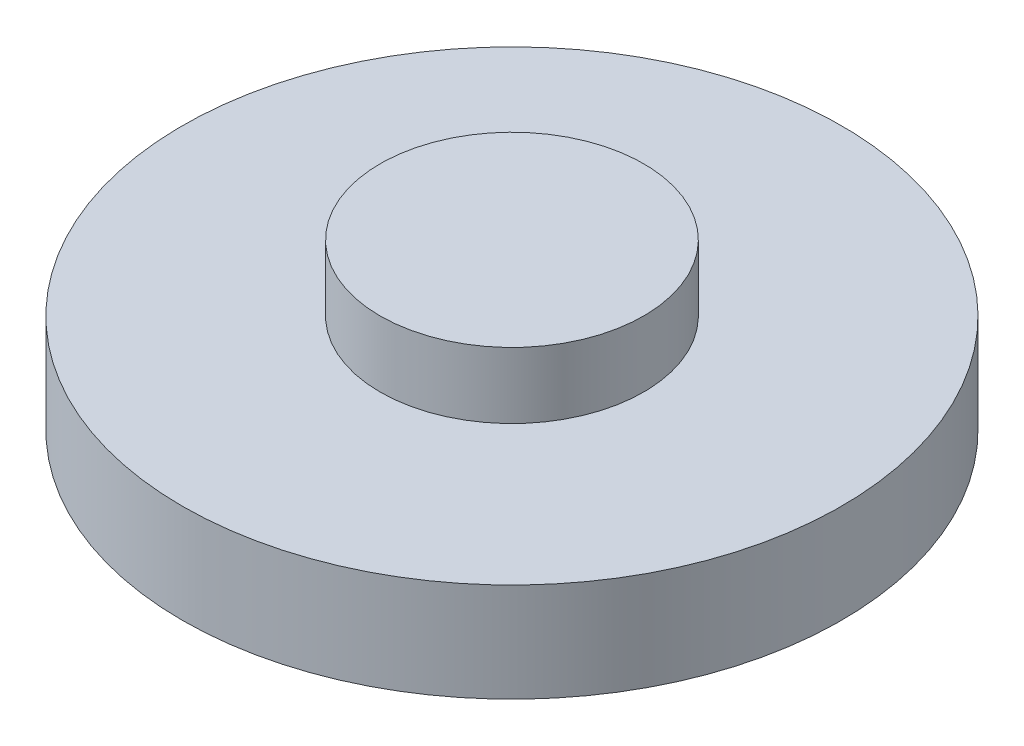
SolidWorks part; units mm, degrees
ref_plane "Спереди" through (0, 0, 0) normal (0, 0, 1) x (1, 0, 0)
ref_plane "Сверху" through (0, 0, 0) normal (0, 1, 0) x (1, 0, 0)
ref_plane "Справа" through (0, 0, 0) normal (1, 0, 0) x (0, 0, -1)
sketch "Эскиз2" plane through (0, 0, 0) normal (0, 1, 0) x (1, 0, 0)
  circle A0 centre (0, 0) radius 50
extrude "Бобышка-Вытянуть1" add sketch "Эскиз2" along normal blind 15 contours A0
sketch "Эскиз5" plane through (0, 15, 0) normal (0, 1, 0) x (1, 0, 0)
  line L0 (16.6095, 47.1606) -> (-23.7511, -67.4386) construction
  line L1 (-48.1789, 13.3714) -> (57.2195, -15.8806) construction
  circle A0 centre (0, 0) radius 50 construction
  circle A1 centre (0, 0) radius 20
extrude "Бобышка-Вытянуть2" add sketch "Эскиз5" along normal blind 10
sketch "Эскиз6" plane through (0, 0, 0) normal (0, -1, 0) x (1, 0, 0)
  line L0 (0, 50) -> (0, -50) construction
  line L1 (-50, 0) -> (50, 0) construction
  line L2 (-31.925, 9) -> (-31.925, -9) construction
  line L3 (31.93, 9) -> (31.93, -9) construction
  circle A0 centre (0, 0) radius 50 construction
  circle A1 centre (31.93, 9) radius 1.5
  circle A2 centre (31.93, -9) radius 1.5
  circle A3 centre (-31.925, 9) radius 1.5
  circle A4 centre (-31.925, -9) radius 1.5
  point P11 (0, 0)
  dimension "D4" = 31.93
  dimension "D1" = 63.855
  dimension "D2" = 18
  dimension "D3" = 9
extrude "Вырез-Вытянуть1" cut sketch "Эскиз6" against normal blind 7
